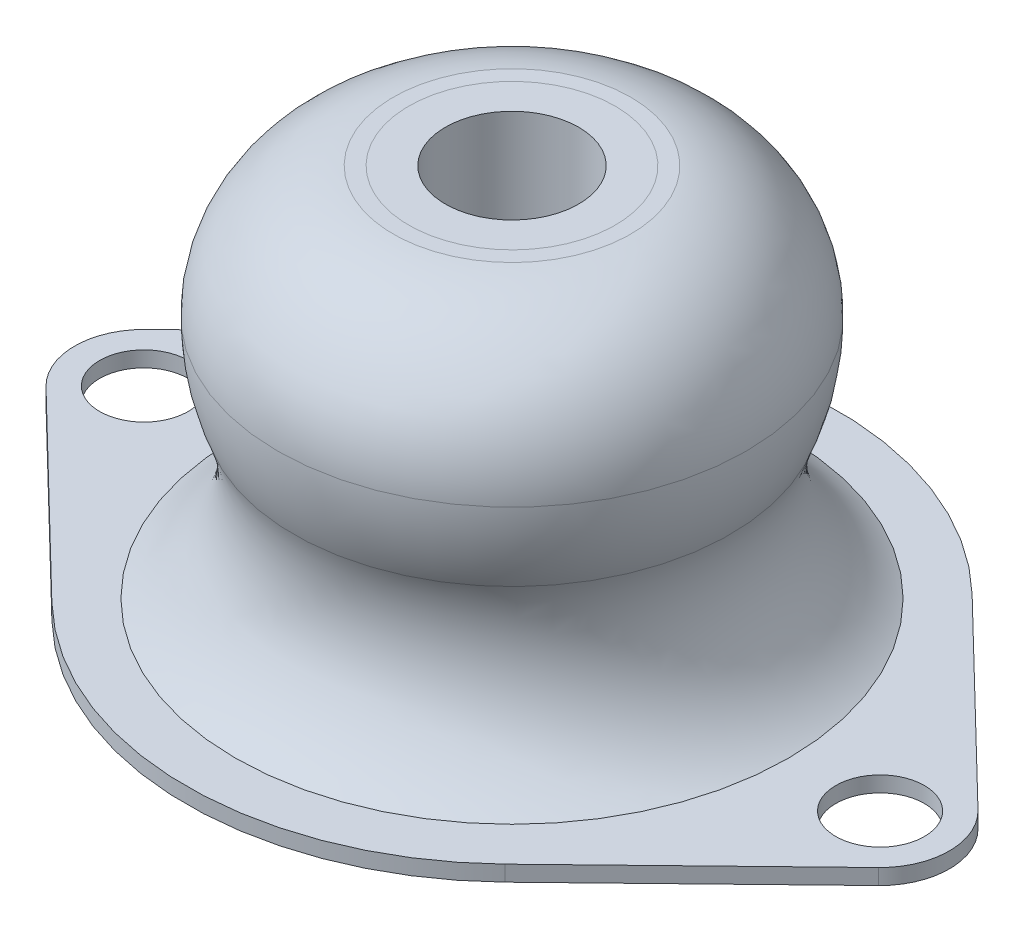
SolidWorks part; units mm, degrees
ref_plane "Front Plane" through (0, 0, 0) normal (0, 0, 1) x (1, 0, 0)
ref_plane "Top Plane" through (0, 0, 0) normal (0, 1, 0) x (1, 0, 0)
ref_plane "Right Plane" through (0, 0, 0) normal (1, 0, 0) x (0, 0, -1)
sketch "Sketch1" plane through (0, 0, 0) normal (0, 0, 1) x (1, 0, 0)
  line L0 (0, -9.525) -> (0, 9.525) construction
  line L1 (-21.336, -9.525) -> (21.336, -9.525) construction
  line L2 (-11.43, 9.525) -> (11.43, 9.525) construction
  line L3 (-3.2512, 3.175) -> (3.2512, 3.175) construction
  line L4 (-21.336, -9.525) -> (-21.336, -8.763) construction
  line L5 (-21.336, -8.763) -> (21.336, -8.763) construction
  line L6 (21.336, -8.763) -> (21.336, -9.525) construction
  line L7 (-17.9578, -9.525) -> (-17.9578, -8.763) construction
  line L8 (17.9578, -9.525) -> (17.9578, -8.763) construction
  line L9 (-11.43, 9.525) -> (-11.43, -8.763) construction
  line L10 (-5.7912, 9.525) -> (-3.2512, 9.525)
  line L11 (-8.255, -3.175) -> (8.255, -3.175) construction
  line L12 (-21.1836, -3.175) -> (-21.1836, -9.525) construction
  line L13 (-21.1836, -3.175) -> (-21.1836, 3.175) construction
  line L16 (-11.43, 3.175) -> (-3.2512, 3.175) construction
  line L18 (-3.2512, 3.175) -> (-3.2512, 9.525)
  line L19 (-5.0351, 3.175) -> (-5.0351, 9.525)
  line L23 (-9.525, -9.525) -> (-9.525, -8.763) construction
  line L24 (-13.4937, -8.763) -> (-9.525, -8.763)
  line L28 (-6.9239, 3.175) -> (-5.0351, 3.175)
  arc A0 (-5.7912, 9.525) -> (-11.43, 3.175) centre (-5.0351, 3.175) ccw
  arc A3 (-11.43, 3.175) -> (-10.6485, -0.7326) centre (-1.2702, 3.175) ccw
  arc A5 (-9.525, -8.763) -> (-8.8214, 0.6097) centre (-21.1836, -3.175) ccw
  arc A8 (-6.9239, 3.175) -> (-8.8214, 0.6097) centre (-6.9239, 1.1906) ccw
  arc A10 (-13.4937, -8.763) -> (-10.6485, -0.7326) centre (-16.5102, -3.175) ccw
  point P5 (-9.525, -9.525)
  point P6 (9.525, -9.525)
  point P7 (0, 9.525)
  point P11 (0, 3.175)
  point P19 (-15.7988, -8.763)
  point P20 (-20.1168, -8.763)
  point P21 (15.875, -9.525)
  point P22 (-15.875, -9.525)
  point P27 (0, -3.175)
  point P42 (-13.4937, -8.763)
  point P53 (-10.16, -3.175)
  dimension "R" = 1.9844
  dimension "Base Length" = 42.672
  dimension "Overall Height" = 19.05
  dimension "Bottom Diameter" = 19.05
  dimension "Diameter" = 22.86
  dimension "Hole Diameter" = 6.5024
  dimension "Hole Depth" = 6.35
  dimension "Base Height" = 0.762
  dimension "Mounting Hole Spacing" = 35.9156
  dimension "Mounting Hole Diameter" = 4.318
  dimension "Base Width" = 31.75
  dimension "Minor Internal ID" = 16.51
  dimension "D1" = 2.54
  dimension "Bottom Rubber Diameter" = 26.9875
  dimension "D2" = 1.27
sketch "Sketch2" plane through (0, 0, 0) normal (0, 0, 1) x (1, 0, 0)
  line L0 (-13.4938, -8.763) -> (-9.525, -8.763) construction
  line L1 (-6.9239, 3.175) -> (-5.0351, 3.175) construction
  line L2 (-13.4938, -8.763) -> (-9.525, -8.763)
  line L3 (-6.9239, 3.175) -> (-5.0351, 3.175)
  line L4 (-5.0351, 3.175) -> (-5.0351, 9.525) construction
  line L5 (-5.0351, 3.175) -> (-5.0351, 9.525)
  line L6 (-5.7912, 9.525) -> (-3.2512, 9.525) construction
  line L7 (-5.7912, 9.525) -> (-5.0351, 9.525)
  line L8 (0, -9.525) -> (0, 9.525) construction
  line L9 (0, -9.525) -> (0, 9.525) construction
  line L10 (5.7912, 9.525) -> (5.0351, 9.525) construction
  line L11 (5.0351, 3.175) -> (5.0351, 9.525) construction
  line L12 (6.9239, 3.175) -> (5.0351, 3.175) construction
  line L13 (13.4938, -8.763) -> (9.525, -8.763) construction
  line L14 (3.2512, 9.525) -> (3.2512, 3.175) construction
  line L15 (-3.2512, 9.525) -> (0, 9.525) construction
  line L16 (0, 9.525) -> (3.2512, 9.525) construction
  arc A0 (-9.525, -8.763) -> (-8.8214, 0.6097) centre (-21.1836, -3.175) ccw construction
  arc A1 (-13.4938, -8.763) -> (-10.6485, -0.7326) centre (-16.5102, -3.175) ccw construction
  arc A2 (-11.43, 3.175) -> (-10.6485, -0.7326) centre (-1.2702, 3.175) ccw construction
  arc A3 (-6.9239, 3.175) -> (-8.8214, 0.6097) centre (-6.9239, 1.1906) ccw construction
  arc A4 (-5.7912, 9.525) -> (-11.43, 3.175) centre (-5.0351, 3.175) ccw construction
  arc A5 (-9.525, -8.763) -> (-8.8214, 0.6097) centre (-21.1836, -3.175) ccw
  arc A6 (-13.4938, -8.763) -> (-10.6485, -0.7326) centre (-16.5102, -3.175) ccw
  arc A7 (-11.43, 3.175) -> (-10.6485, -0.7326) centre (-1.2702, 3.175) ccw
  arc A8 (-6.9239, 3.175) -> (-8.8214, 0.6097) centre (-6.9239, 1.1906) ccw
  arc A9 (-5.7912, 9.525) -> (-11.43, 3.175) centre (-5.0351, 3.175) ccw
  arc A10 (5.7912, 9.525) -> (11.43, 3.175) centre (5.0351, 3.175) cw construction
  arc A11 (6.9239, 3.175) -> (8.8214, 0.6097) centre (6.9239, 1.1906) cw construction
  arc A12 (11.43, 3.175) -> (10.6485, -0.7326) centre (1.2702, 3.175) cw construction
  arc A13 (13.4938, -8.763) -> (10.6485, -0.7326) centre (16.5102, -3.175) cw construction
  arc A14 (9.525, -8.763) -> (8.8214, 0.6097) centre (21.1836, -3.175) cw construction
revolve "Revolve1" add sketch "Sketch2" angle 360 about L0
sketch "Sketch3" plane through (0, 0, 0) normal (0, 0, 1) x (1, 0, 0)
  line L0 (-11.43, 3.175) -> (-3.2512, 3.175) construction
  line L1 (-3.2512, 3.175) -> (-3.2512, 9.525) construction
  line L2 (-5.7912, 9.525) -> (-3.2512, 9.525) construction
  line L3 (-5.0351, 3.175) -> (-5.0351, 9.525) construction
  line L4 (-5.0351, 3.175) -> (-3.2512, 3.175)
  line L5 (-3.2512, 3.175) -> (-3.2512, 9.525)
  line L6 (-5.0351, 9.525) -> (-3.2512, 9.525)
  line L7 (-5.0351, 3.175) -> (-5.0351, 9.525)
revolve "Revolve2" add sketch "Sketch3" angle 360 about L0
sketch "Sketch4" plane through (0, 0, 0) normal (0, -1, 0) x (1, 0, 0)
  line L0 (-20.3087, -2.426) -> (-11.0474, -11.4005)
  line L1 (-20.3087, 2.426) -> (-11.0474, 11.4005)
  line L2 (20.3087, 2.426) -> (11.0474, 11.4005)
  line L3 (20.3087, -2.426) -> (11.0474, -11.4005)
  line L4 (-21.336, 0) -> (21.336, 0) construction
  arc A0 (11.0474, 11.4005) -> (-11.0474, 11.4005) centre (0, 0) ccw
  circle A1 centre (-17.9578, 0) radius 2.159
  circle A2 centre (17.9578, 0) radius 2.159
  arc A3 (-20.3087, 2.426) -> (-20.3087, -2.426) centre (-17.9578, 0) ccw
  arc A4 (20.3087, -2.426) -> (20.3087, 2.426) centre (17.9578, 0) ccw
  arc A5 (-11.0474, -11.4005) -> (11.0474, -11.4005) centre (0, 0) ccw
  circle A6 centre (0, 0) radius 9.525
  point P1 (0, 15.875)
  point P8 (0, -15.875)
extrude "Boss-Extrude1" add sketch "Sketch4" against normal blind 0.762 from vertex at 9.525 separate body starting at point (-9.525, -9.525, 0)
equation "\"D1@Sketch1\"=\"Diameter@Sketch1\"/9"
equation "\"D2@Sketch1\"=\"Diameter@Sketch1\"/18"
equation "\"D1@Boss-Extrude1\"=\"Base Height@Sketch1\""
